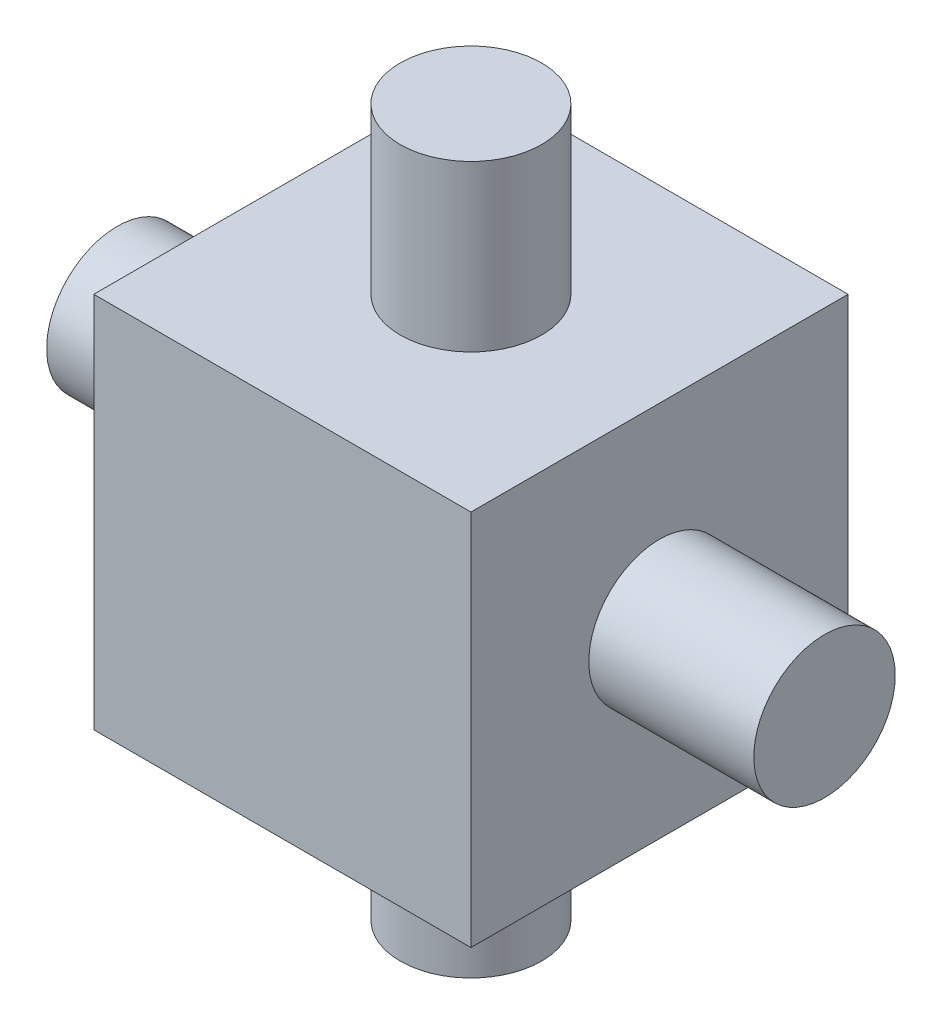
SolidWorks part; units mm, degrees
material "1060 Alloy"
ref_plane "Front Plane" through (0, 0, 0) normal (0, 0, 1) x (1, 0, 0)
ref_plane "Top Plane" through (0, 0, 0) normal (0, 1, 0) x (1, 0, 0)
ref_plane "Right Plane" through (0, 0, 0) normal (1, 0, 0) x (0, 0, -1)
sketch "Sketch1" plane through (0, 0, 0) normal (0, 0, 1) x (1, 0, 0)
  line L1 (20, -20) -> (-20, -20)
  line L2 (20, -20) -> (20, 20)
  line L3 (20, 20) -> (-20, 20)
  line L4 (-20, -20) -> (-20, 20)
  line L5 (20, -20) -> (-20, 20) construction
  line L6 (20, 20) -> (-20, -20) construction
  point P0 (0, 0)
  dimension "D1" = 40
  dimension "D2" = 40
extrude "Boss-Extrude1" add sketch "Sketch1" along normal blind 40
sketch "Sketch2" plane through (0, 20, 0) normal (0, 1, 0) x (1, 0, 0)
  line L0 (-20, -20) -> (20, -20) construction
  line L1 (-20, -40) -> (-20, 0) construction
  line L2 (20, -40) -> (20, 0) construction
  circle A0 centre (0, -20) radius 7.5
  point P8 (0, -25)
  dimension "D1" = 15
extrude "Boss-Extrude2" add sketch "Sketch2" along normal blind 17.5
mirror "Mirror1" about plane through (0, 0, 0) normal (0, 1, 0) of "Boss-Extrude2"
sketch "Sketch3" plane through (20, 0, 0) normal (1, 0, 0) x (0, 0, -1)
  line L0 (-20, 20) -> (-20, -25.9633) construction
  line L1 (-40, 20) -> (0, 20) construction
  circle A0 centre (-20, 0) radius 7.5
  point P6 (-25, 0)
  dimension "D1" = 15
extrude "Boss-Extrude3" add sketch "Sketch3" along normal blind 17.5
mirror "Mirror2" about plane through (0, 0, 0) normal (1, 0, 0) of "Boss-Extrude3"
